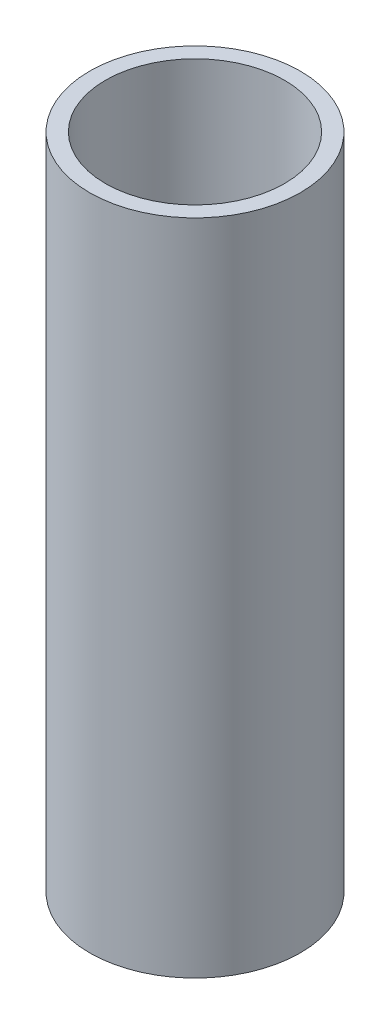
SolidWorks part; units mm, degrees
ref_plane "Front Plane" through (0, 0, 0) normal (0, 0, 1) x (1, 0, 0)
ref_plane "Top Plane" through (0, 0, 0) normal (0, 1, 0) x (1, 0, 0)
ref_plane "Right Plane" through (0, 0, 0) normal (1, 0, 0) x (0, 0, -1)
sketch "Sketch1" plane through (0, 0, 0) normal (0, 1, 0) x (1, 0, 0)
  circle A0 centre (0, 0) radius 8
  circle A1 centre (0, 0) radius 6.8
  dimension "D1" = 1.2
  dimension "D2" = 16
extrude "Boss-Extrude1" add sketch "Sketch1" along normal blind 50
sketch "Sketch2" plane through (0, 0, 0) normal (1, 0, 0) x (0, 0, -1)
  line L0 (0, 0) -> (0, 50) construction
  line L1 (8, 50) -> (-8, 50) construction
  circle A0 centre (0, 25) radius 0.5
  point P8 (0, 25)
  dimension "D1" = 1
extrude "Cut-Extrude1" cut sketch "Sketch2" against normal through all
